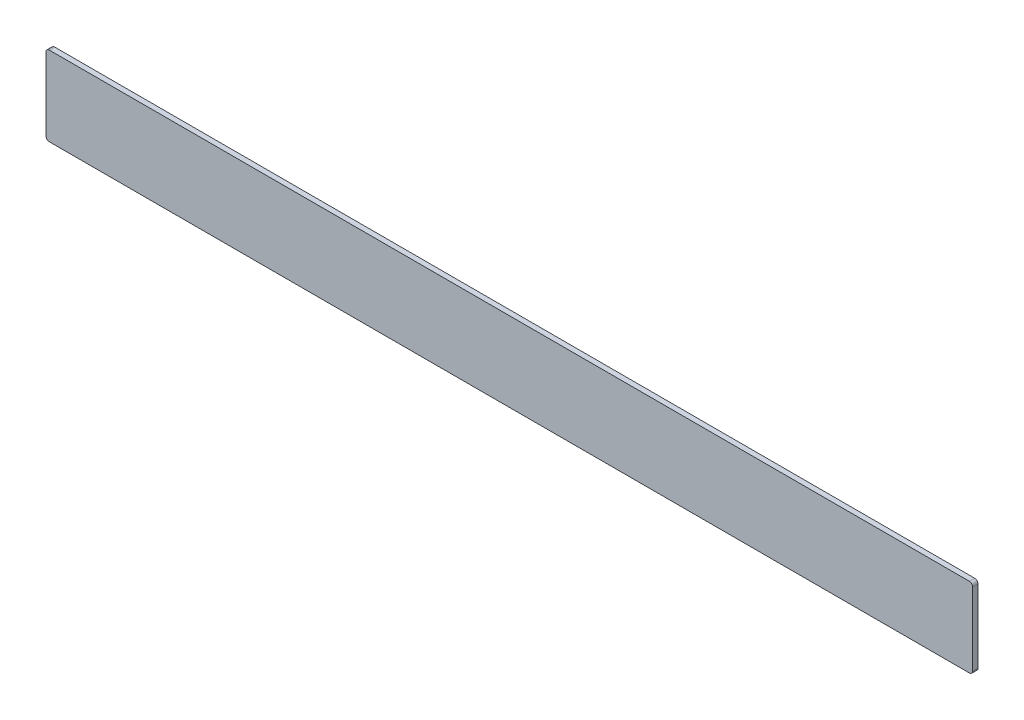
SolidWorks part; units mm, degrees
ref_plane "Front Plane" through (0, 0, 0) normal (0, 0, 1) x (1, 0, 0)
ref_plane "Top Plane" through (0, 0, 0) normal (0, 1, 0) x (1, 0, 0)
ref_plane "Right Plane" through (0, 0, 0) normal (1, 0, 0) x (0, 0, -1)
sketch "Sketch1" plane through (0, 0, 0) normal (0, 0, 1) x (1, 0, 0)
  line L1 (700, -60) -> (-700, -60)
  line L2 (700, -60) -> (700, 60)
  line L3 (700, 60) -> (-700, 60)
  line L4 (-700, -60) -> (-700, 60)
  line L5 (700, -60) -> (-700, 60) construction
  line L6 (700, 60) -> (-700, -60) construction
  point P0 (0, 0)
  dimension "D1" = 1400
  dimension "D2" = 120
extrude "Boss-Extrude1" add sketch "Sketch1" along normal blind 8
fillet "Fillet1" radius 5 4 edges at (-700, -60, 4) (-700, 60, 4) (700, -60, 4) (700, 60, 4)
